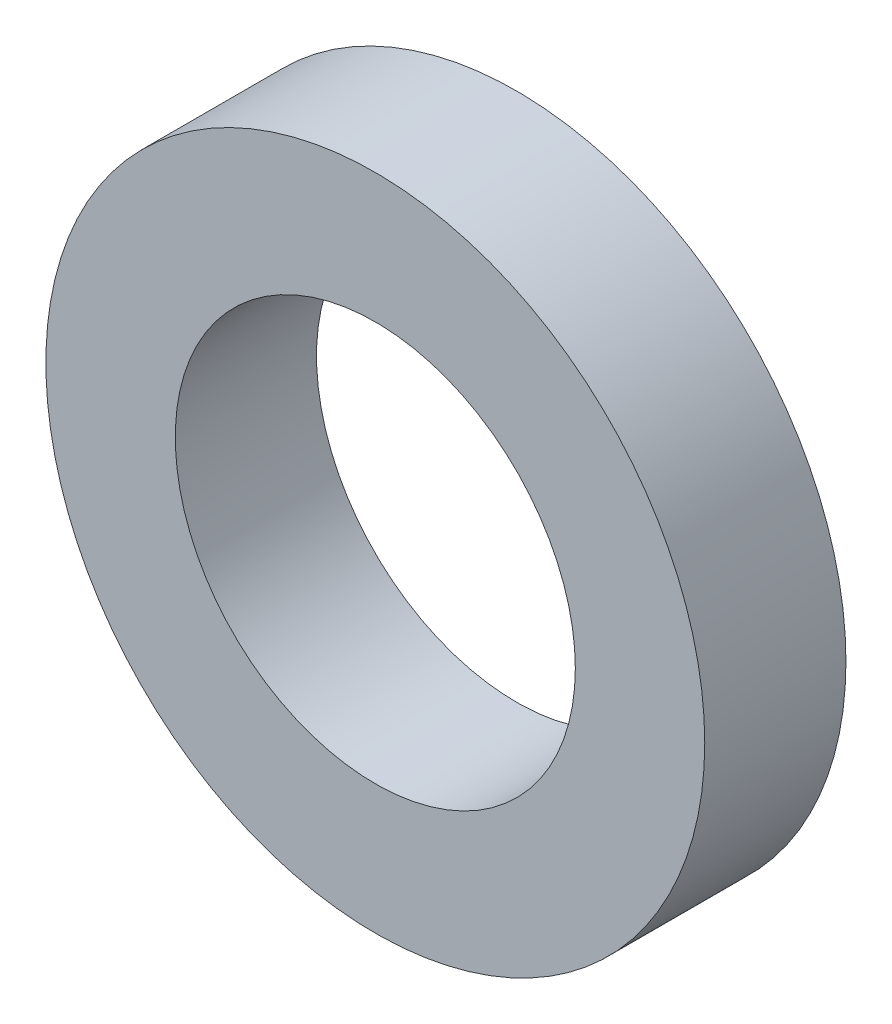
SolidWorks part; units mm, degrees
ref_plane "Plan de face" through (0, 0, 0) normal (0, 0, 1) x (1, 0, 0)
ref_plane "Plan de dessus" through (0, 0, 0) normal (0, 1, 0) x (1, 0, 0)
ref_plane "Plan de droite" through (0, 0, 0) normal (1, 0, 0) x (0, 0, -1)
sketch "Esquisse1" plane through (0, 0, 0) normal (0, 0, 1) x (1, 0, 0)
  circle A0 centre (0, 0) radius 7
  circle A1 centre (0, 0) radius 4.25
  dimension "D1" = 8.5
  dimension "D2" = 14
extrude "Boss.-Extru.1" add sketch "Esquisse1" along normal blind 3
